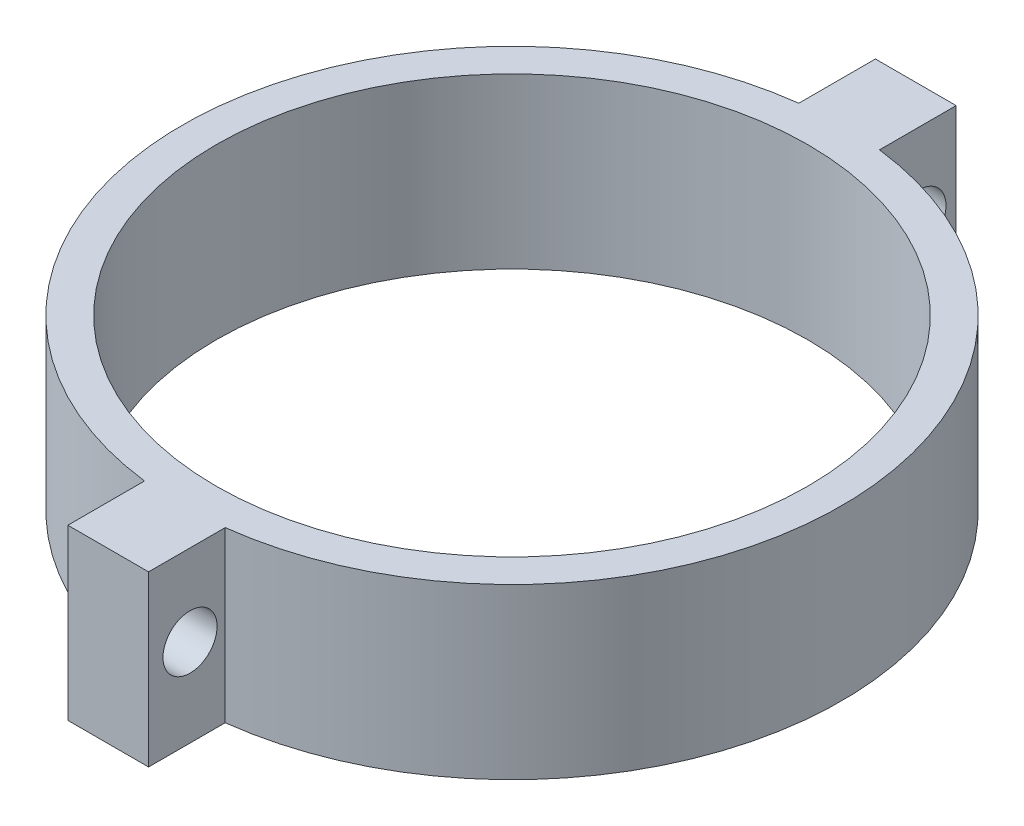
SolidWorks part; units mm, degrees
ref_plane "Front Plane" through (0, 0, 0) normal (0, 0, 1) x (1, 0, 0)
ref_plane "Top Plane" through (0, 0, 0) normal (0, 1, 0) x (1, 0, 0)
ref_plane "Right Plane" through (0, 0, 0) normal (1, 0, 0) x (0, 0, -1)
sketch "Sketch2" plane through (0, 0, 0) normal (0, 1, 0) x (1, 0, 0)
  line L0 (0, 0) -> (-27.8248, 0) construction
  line L1 (0, 0) -> (0, 11.1136) construction
  line L2 (2.3875, 19.3533) -> (2.3875, 23.8864)
  line L5 (2.3875, 23.8864) -> (-2.3875, 23.8864)
  line L7 (-0.7424, -19.4859) -> (-2.3875, -23.8864) construction
  line L8 (2.3875, 23.8864) -> (0.7424, 19.4859) construction
  line L9 (2.3875, -23.8864) -> (0.7424, -19.4859) construction
  line L10 (0, 19.5) -> (0, 29.5407) construction
  line L11 (-0.7424, 19.4859) -> (-2.3875, 23.8864) construction
  line L12 (-2.3875, 19.3533) -> (-2.3875, 23.8864)
  line L13 (-2.3875, -19.3533) -> (-2.3875, -23.8864)
  line L14 (2.3875, -23.8864) -> (-2.3875, -23.8864)
  line L15 (2.3875, -19.3533) -> (2.3875, -23.8864)
  circle A0 centre (0, 0) radius 17.5
  circle A1 centre (0, 0) radius 19.5
  point P4 (0, 17.5)
  dimension "D1" = 35
  dimension "D2" = 39
  dimension "D3" = 4.5332
extrude "Boss-Extrude2" add sketch "Sketch2" along normal blind 10 contours A1 A0 | A1 L2 L5 L12 | A1 L13 L14 L15
sketch "Sketch3" plane through (-2.3875, 0, 0) normal (-1, 0, 0) x (0, 0, 1)
  circle A0 centre (-21.6874, 5.1828) radius 1.6
  circle A1 centre (21.434, 5.1828) radius 1.6
  dimension "D1" = 3.2
  dimension "D2" = 3.2
extrude "Cut-Extrude1" cut sketch "Sketch3" against normal blind 10
